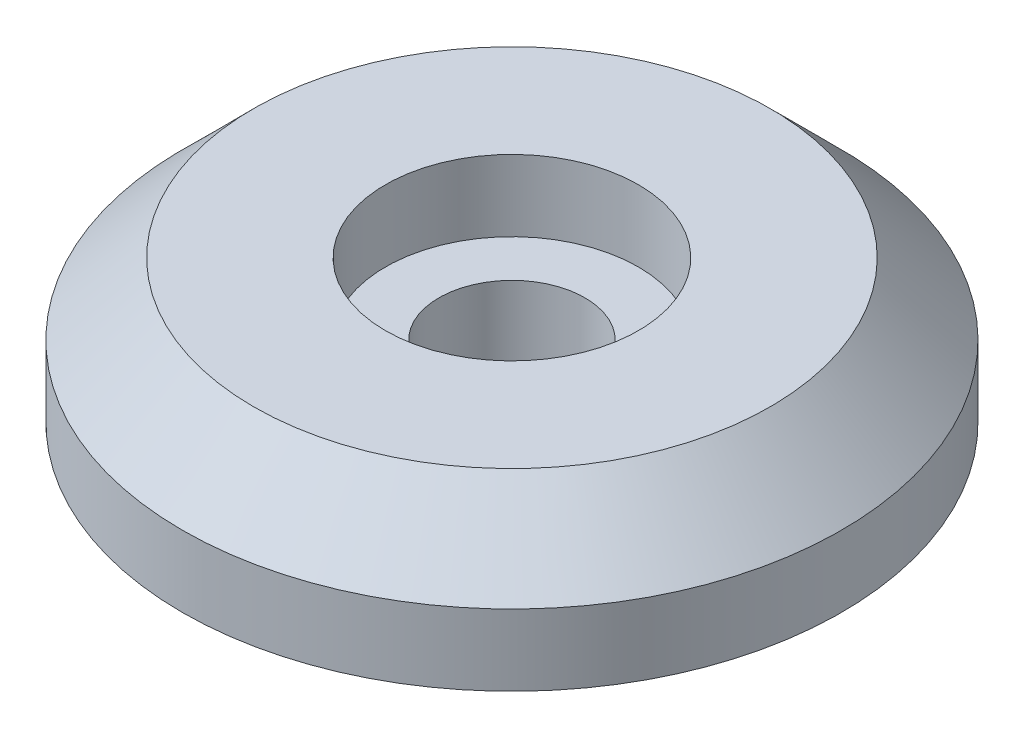
SolidWorks part; units mm, degrees
material "PLA Infill"
ref_plane "Front Plane" through (0, 0, 0) normal (0, 0, 1) x (1, 0, 0)
ref_plane "Top Plane" through (0, 0, 0) normal (0, 1, 0) x (1, 0, 0)
ref_plane "Right Plane" through (0, 0, 0) normal (1, 0, 0) x (0, 0, -1)
sketch "Sketch1" plane through (0, 0, 0) normal (0, 1, 0) x (1, 0, 0)
  circle A0 centre (0, 0) radius 9.25
  circle A1 centre (0, 0) radius 2.05
  dimension "D1" = 18.5
  dimension "D2" = 4.1
extrude "Boss-Extrude1" add sketch "Sketch1" along normal blind 4
sketch "Sketch2" plane through (0, 4, 0) normal (0, 1, 0) x (1, 0, 0)
  circle A0 centre (0, 0) radius 3.55
  dimension "D1" = 7.1
extrude "Cut-Extrude1" cut sketch "Sketch2" against normal blind 2
chamfer "Chamfer1" distance 2 angle 45 1 edges at (0, 4, 9.25)
